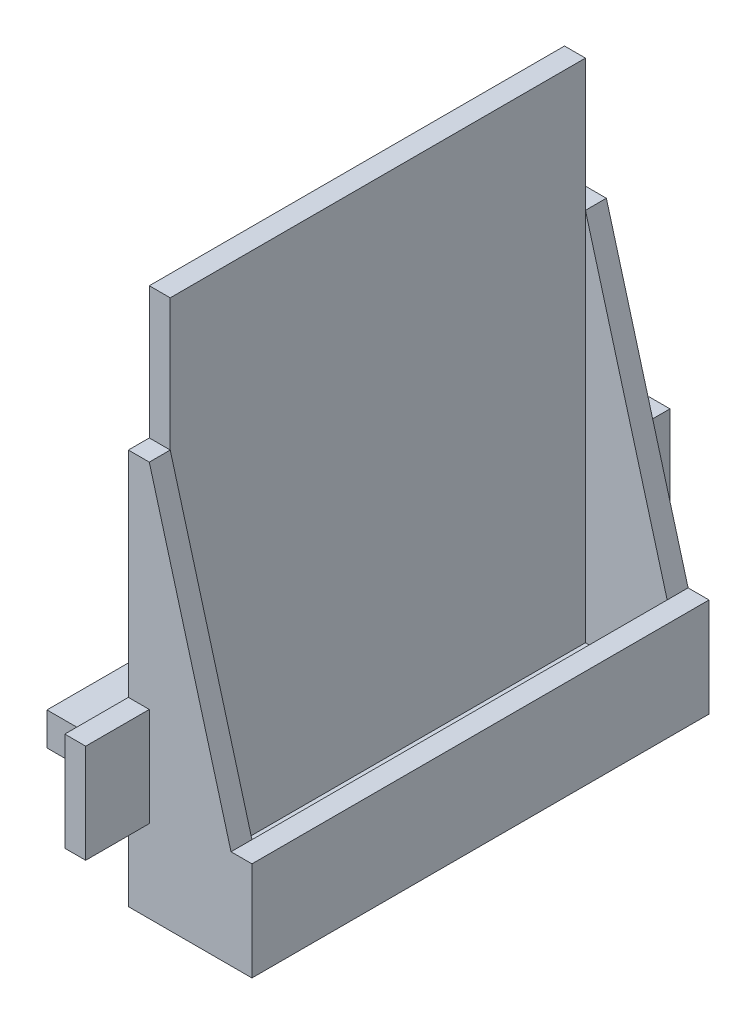
SolidWorks part; units mm, degrees
ref_plane "Front Plane" through (0, 0, 0) normal (0, 0, 1) x (1, 0, 0)
ref_plane "Top Plane" through (0, 0, 0) normal (0, 1, 0) x (1, 0, 0)
ref_plane "Right Plane" through (0, 0, 0) normal (1, 0, 0) x (0, 0, -1)
sketch "Sketch2" plane through (0, 0, 0) normal (1, 0, 0) x (0, 0, -1)
  line L0 (-22.5, 0) -> (0, 0) construction
  line L1 (-22.5, 2.5) -> (-22.5, -2.5)
  line L2 (-22.5, -2.5) -> (-37.5, -2.5)
  line L3 (-37.5, -2.5) -> (-37.5, 2.5)
  line L4 (-37.5, 2.5) -> (-22.5, 2.5)
  line L5 (0, 18.786) -> (0, -13.8397) construction
  dimension "D1" = 22.5
  dimension "D2" = 5
  dimension "D3" = 15
extrude "Boss-Extrude1" add sketch "Sketch2" along normal mid plane 9.525
mirror "Mirror4" about plane through (0, 0, 0) normal (0, 0, 1) of bodies 101
sketch "Sketch4" plane through (4.7625, 0, 0) normal (1, 0, 0) x (0, 0, -1)
  line L0 (0, 60) -> (0, -20) construction
  line L1 (31.5153, 7.5087) -> (44.325, 7.5)
  line L2 (-44.325, 0) -> (44.325, 0) construction
  line L3 (-37.9125, 7.5) -> (-37.9125, -7.5) construction
  line L4 (-44.325, -7.5) -> (-31.5, -7.5)
  line L5 (-44.325, 7.5) -> (-31.5, 7.5)
  line L6 (-31.5, 7.5) -> (-31.5, -7.5) construction
  line L9 (-31.5, -7.5) -> (-31.5, -20)
  line L11 (-31.5, 60) -> (-31.5, 7.5)
  line L12 (-44.325, -7.5) -> (-44.325, 7.5)
  line L16 (-31.5, -20) -> (31.5, -20)
  line L17 (-31.5, 60) -> (31.5, 60)
  line L26 (31.5, 7.5) -> (31.5153, 7.5087)
  line L27 (44.325, -7.5) -> (44.325, 7.5)
  line L28 (31.5, 60) -> (31.5, 7.5)
  line L29 (31.5, -7.5) -> (31.5, -20)
  line L31 (44.325, -7.5) -> (31.5, -7.5)
  dimension "D1" = 63
  dimension "D2" = 12.825
  dimension "D3" = 52.5
  dimension "D4" = 15
  dimension "D5" = 12.5
extrude "Boss-Extrude3" add sketch "Sketch4" along normal blind 3.175 separate body
sketch "Sketch6" plane through (4.7625, 0, 0) normal (1, 0, 0) x (0, 0, -1)
  line L0 (-31.5, 40) -> (-31.5, -16.825)
  line L1 (-31.5, 40) -> (31.5, 40) construction
  line L2 (-34.675, -20) -> (34.675, -20)
  line L3 (31.5, 40) -> (34.675, 40)
  line L4 (-31.5, -7.5) -> (-31.5, -20) construction
  line L5 (-34.675, -20) -> (-34.675, 40)
  line L6 (-31.5, -16.825) -> (31.5, -16.825)
  line L7 (0, 60) -> (0, -20) construction
  line L8 (-31.5, -20) -> (31.5, -20) construction
  line L9 (0, 60) -> (0, -20) construction
  line L10 (-31.5, 60) -> (31.5, 60) construction
  line L14 (-34.675, 40) -> (-31.5, 40)
  line L15 (34.675, 40) -> (34.675, -20)
  line L16 (31.5, 40) -> (31.5, -16.825)
  point P18 (0, -16.825)
  dimension "D1" = 3.175
  dimension "D2" = 3.175
  dimension "D3" = 60
extrude "Boss-Extrude5" add sketch "Sketch6" along normal blind 15.575
sketch "Sketch7" plane through (20.3375, 0, 0) normal (1, 0, 0) x (0, 0, -1)
  line L0 (-34.675, -20) -> (-34.675, -5)
  line L2 (-34.675, -5) -> (34.675, -5)
  line L4 (34.675, -5) -> (34.675, -20)
  line L5 (-34.675, -20) -> (34.675, -20) construction
  line L6 (34.675, -20) -> (-34.675, -20)
  dimension "D1" = 15
extrude "Boss-Extrude6" add sketch "Sketch7" along normal blind 3.175
sketch "Sketch8" plane through (0, -16.825, 0) normal (0, 1, 0) x (1, 0, 0)
  line L0 (7.9375, 31.5) -> (20.3375, 31.5) construction
  line L1 (20.3375, 29.7961) -> (19.3375, 29.7961) construction
  line L2 (20.3375, 31.5) -> (20.3375, -31.5) construction
  line L3 (19.3375, 31.5) -> (19.3375, -31.5) construction
  line L4 (14.1375, 31.5) -> (14.1375, -31.5) construction
  line L5 (7.9375, 0) -> (14.0875, 0) construction
  line L6 (7.9375, -31.5) -> (20.3375, -31.5) construction
  line L7 (7.9375, 31.5) -> (7.9375, -31.5) construction
  line L8 (14.0875, 0) -> (14.0875, 11.05) construction
  line L9 (15.6375, 11.05) -> (12.5375, 11.05)
  line L10 (12.5375, 11.05) -> (12.5375, -11.05)
  line L11 (15.6375, 11.05) -> (15.6375, -11.05)
  line L12 (12.5375, -11.05) -> (15.6375, -11.05)
  dimension "D1" = 12.4
  dimension "D2" = 1
  dimension "D3" = 6.15
  dimension "D4" = 11.05
  dimension "D5" = 1.55
  dimension "D6" = 3.1
  dimension "D7" = 22.1
extrude "Cut-Extrude1" cut sketch "Sketch8" against normal up to next (3.175 mm away)
sketch "Sketch10" plane through (0, 0, 34.675) normal (0, 0, 1) x (1, 0, 0)
  line L0 (7.9375, 40) -> (20.3375, -5)
  line L1 (7.9375, 60) -> (7.9375, 7.5) construction
  line L2 (20.3375, 40) -> (4.7625, 40) construction
  line L3 (7.9375, 40) -> (20.3375, 40)
  line L4 (20.3375, 40) -> (20.3375, -5)
extrude "Cut-Extrude2" cut sketch "Sketch10" against normal through all
